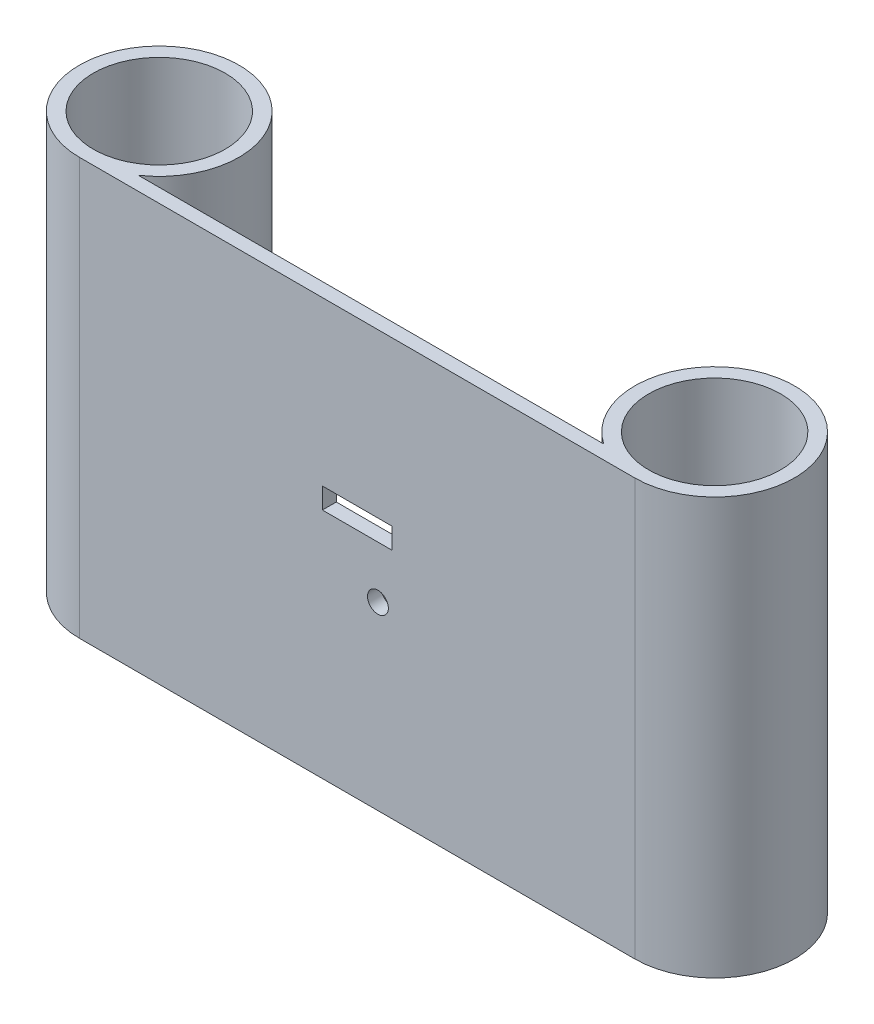
SolidWorks part; units mm, degrees
ref_plane "Front Plane" through (0, 0, 0) normal (0, 0, 1) x (1, 0, 0)
ref_plane "Top Plane" through (0, 0, 0) normal (0, 1, 0) x (1, 0, 0)
ref_plane "Right Plane" through (0, 0, 0) normal (1, 0, 0) x (0, 0, -1)
sketch "Sketch1" plane through (0, 0, 0) normal (0, 1, 0) x (1, 0, 0)
  line L1 (-40, 11.5) -> (40, 11.5)
  line L3 (-40, -11.5) -> (40, -11.5)
  line L5 (-40, 11.5) -> (40, -11.5) construction
  line L6 (-40, -11.5) -> (40, 11.5) construction
  arc A0 (-40, 11.5) -> (-40, -11.5) centre (-40, 0) ccw
  arc A1 (40, 11.5) -> (40, -11.5) centre (40, 0) cw
  point P0 (0, 0)
  dimension "D1" = 80
  dimension "D2" = 23
extrude "Boss-Extrude1" add sketch "Sketch1" along normal blind 60
sketch "Sketch2" plane through (0, 0, 0) normal (0, -1, 0) x (1, 0, 0)
  circle A1 centre (-40, 0) radius 9.5
  circle A2 centre (40, 0) radius 9.5
  dimension "D1" = 19
extrude "Cut-Extrude1" cut sketch "Sketch2" against normal blind 60
sketch "Sketch3" plane through (0, 0, 0) normal (0, -1, 0) x (1, 0, 0)
  line L0 (-33.5193, 9.5) -> (33.5193, 9.5)
  line L1 (-40, 11.5) -> (40, 11.5) construction
  line L2 (-40, -11.5) -> (40, -11.5)
  circle A2 centre (-40, 0) radius 11.5
  circle A3 centre (40, 0) radius 11.5
  point P5 (0, 0)
  point P15 (0, 0)
  point P18 (0, 0)
  point P19 (0, 0)
  point P21 (0, 0)
  point P22 (0, 0)
  point P23 (0, 0)
  line M10 (-40, -11.5) -> (40, -11.5)
  dimension "D2" = 23
  dimension "D3" = 11.5
  dimension "D1" = 2
  dimension "D4" = 11.5
extrude "Cut-Extrude2" cut sketch "Sketch3" against normal blind 60 contours A3 L0 A2 M10
sketch "Sketch4" plane through (0, 0, 0) normal (0, -1, 0) x (1, 0, 0)
  line L1 (-33.5193, 9.5) -> (33.5193, 9.5)
  arc A0 (12.8195, -4.232) -> (-12.8195, -4.232) centre (0, 0) cw
  arc A3 (-33.5193, 9.5) -> (-12.8195, -4.232) centre (-33.5193, -12.9675) cw
  arc A4 (33.5193, 9.5) -> (12.8195, -4.232) centre (33.5193, -12.9675) ccw
  dimension "D2" = 13.5
  dimension "D3" = 22.4675
  dimension "D4" = 22.4675
  dimension "D1" = 0
extrude "Boss-Extrude3" add sketch "Sketch4" against normal blind 3
sketch "Sketch5" plane through (0, 0, 0) normal (0, -1, 0) x (1, 0, 0)
  line L0 (-33.5193, 9.5) -> (33.5193, 9.5)
  arc A0 (6.4807, 9.5) -> (-6.4807, 9.5) centre (0, 0) cw
  circle A1 centre (0, 0) radius 4.1
  dimension "D1" = 0
  dimension "D2" = 11.5
  dimension "D4" = 8.2
  dimension "D3" = 0
extrude "Cut-Extrude3" cut sketch "Sketch5" against normal blind 3 contours A1
sketch "Sketch6" plane through (0, 0, 0) normal (0, -1, 0) x (1, 0, 0)
  line L0 (-33.5193, 9.5) -> (33.5193, 9.5)
  arc A0 (6.4807, 9.5) -> (-6.4807, 9.5) centre (0, 0) cw
  circle A1 centre (5.9792, -6.0415) radius 1.5
  circle A2 centre (-6.0208, -6) radius 1.5
  circle A3 centre (-6.0208, 6) radius 1.5
  circle A4 centre (5.9792, 6.0415) radius 1.5
  dimension "D2" = 8.5
  dimension "D3" = 8.5
  dimension "D9" = 11.5
  dimension "D11" = 3
  dimension "D1" = 8.5
  dimension "D4" = 8.5
  dimension "D5" = 12
  dimension "D6" = 0
  dimension "D7" = 12
  dimension "D8" = 12
  dimension "D10" = 0
extrude "Cut-Extrude4" cut sketch "Sketch6" against normal blind 3 contours A2 | A1 | A4 | A3
sketch "Sketch8" plane through (0, 0, 11.5) normal (0, 0, 1) x (1, 0, 0)
  line L1 (5, 33.5) -> (-5, 33.5)
  line L2 (5, 33.5) -> (5, 36.5)
  line L3 (5, 36.5) -> (-5, 36.5)
  line L4 (-5, 33.5) -> (-5, 36.5)
  line L5 (5, 33.5) -> (-5, 36.5) construction
  line L6 (5, 36.5) -> (-5, 33.5) construction
  circle A0 centre (3, 26) radius 1.5
  point P0 (0, 35)
  point P5 (0, 33.5)
  dimension "D5" = 3
  dimension "D1" = 35
  dimension "D2" = 0
  dimension "D3" = 3
  dimension "D4" = 10
  dimension "D6" = 9
  dimension "D7" = 3
extrude "Cut-Extrude5" cut sketch "Sketch8" against normal blind 3
fillet "Fillet1" radius 1 1 edges at (-40, 0, -9.5)
